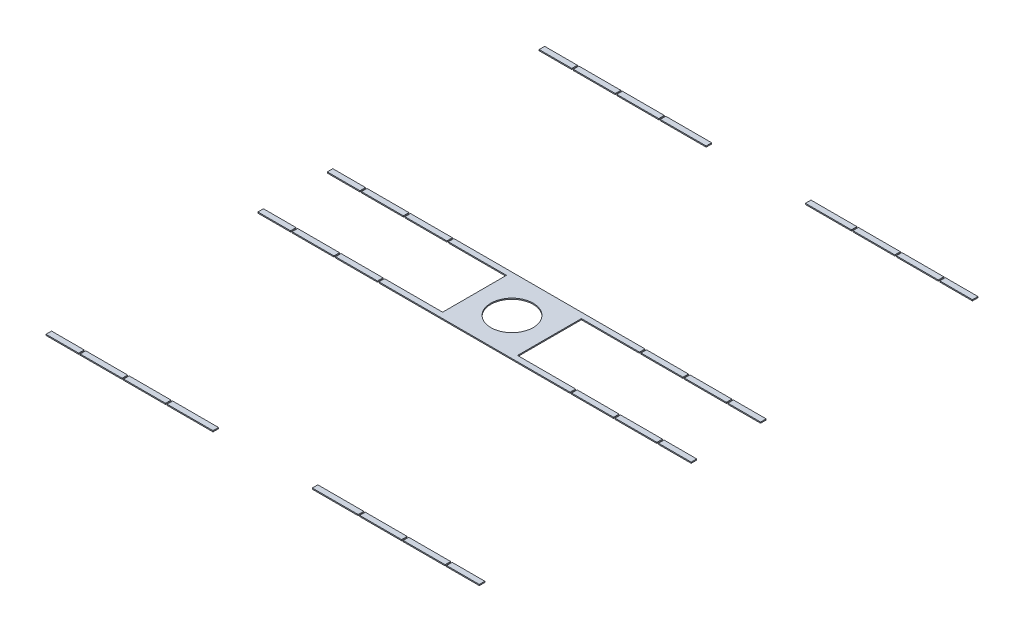
SolidWorks part; units mm, degrees
ref_plane "Front Plane" through (0, 0, 0) normal (0, 0, 1) x (1, 0, 0)
ref_plane "Top Plane" through (0, 0, 0) normal (0, 1, 0) x (1, 0, 0)
ref_plane "Right Plane" through (0, 0, 0) normal (1, 0, 0) x (0, 0, -1)
sketch "Sketch1" plane through (0, 0, 0) normal (0, 1, 0) x (1, 0, 0)
  line L0 (-55, 0) -> (55, 0) construction
  line L1 (-11.225, -11.225) -> (11.225, -11.225)
  line L2 (-11.225, -11.225) -> (-11.225, 11.225)
  line L3 (-11.225, 11.225) -> (11.225, 11.225)
  line L4 (11.225, -11.225) -> (11.225, 11.225)
  line L5 (-11.225, -11.225) -> (11.225, 11.225) construction
  line L6 (-11.225, 11.225) -> (11.225, -11.225) construction
  line L7 (-11.225, 11.225) -> (-1.725, 11.225)
  line L8 (-11.225, 11.225) -> (-11.225, 1.725)
  line L9 (-11.225, 1.725) -> (-1.725, 1.725)
  line L11 (-2.45, 11.73) -> (2.45, 11.73)
  line L12 (-11.225, -1.725) -> (-1.725, -1.725)
  line L13 (0, -55) -> (0, 55) construction
  line L14 (-11.73, -2.45) -> (-11.98, -2.45)
  line L15 (11.225, -1.725) -> (1.725, -1.725)
  line L16 (-11.73, -2.45) -> (-11.73, 2.45)
  line L17 (11.225, 1.725) -> (1.725, 1.725)
  line L18 (-1.725, 1.47) -> (-11.225, 1.47)
  line L19 (11.48, -11.48) -> (-11.48, -11.48)
  line L20 (11.48, -11.48) -> (11.48, 11.48)
  line L21 (11.48, 11.48) -> (-11.48, 11.48)
  line L22 (-11.48, -11.48) -> (-11.48, 11.48)
  line L23 (11.48, -11.48) -> (-11.48, 11.48) construction
  line L24 (11.48, 11.48) -> (-11.48, -11.48) construction
  line L25 (11.225, -1.47) -> (1.725, -1.47)
  line L26 (11.225, -1.47) -> (11.225, 1.47)
  line L27 (11.225, 1.47) -> (1.725, 1.47)
  line L28 (-11.225, -1.47) -> (-11.225, 1.47)
  line L29 (11.225, -1.47) -> (-11.225, 1.47) construction
  line L30 (11.225, 1.47) -> (-11.225, -1.47) construction
  line L31 (-1.225, -11.225) -> (1.225, -11.225)
  line L33 (-1.225, 11.225) -> (1.225, 11.225)
  line L35 (-11.73, 2.45) -> (-11.98, 2.45)
  line L36 (-11.98, -2.45) -> (-11.98, 2.45)
  line L38 (-1.725, -1.47) -> (-11.225, -1.47)
  line L40 (-11.48, 0) -> (-15.585, 0) construction
  line L41 (1.725, 1.725) -> (-1.725, 1.725)
  line L42 (1.725, 1.725) -> (1.725, -1.725)
  line L43 (1.725, -1.725) -> (-1.725, -1.725)
  line L44 (-1.725, 1.725) -> (-1.725, -1.725)
  line L45 (1.725, 1.725) -> (-1.725, -1.725) construction
  line L46 (1.725, -1.725) -> (-1.725, 1.725) construction
  line L47 (-11.48, -2.45) -> (-11.73, -2.45)
  line L48 (-11.48, 1.45) -> (-11.73, 1.45)
  line L49 (-11.48, 1.45) -> (-11.48, 2.45)
  line L50 (-11.48, 2.45) -> (-11.73, 2.45)
  line L51 (-11.73, 1.45) -> (-11.73, 2.45)
  line L52 (-11.73, -1.45) -> (-11.73, -2.45)
  line L53 (-11.48, -1.45) -> (-11.73, -1.45)
  line L54 (-11.48, -1.45) -> (-11.48, -2.45)
  line L55 (1.45, 11.48) -> (2.45, 11.48)
  line L56 (1.45, 11.48) -> (1.45, 11.73)
  line L57 (1.45, 11.73) -> (2.45, 11.73)
  line L58 (2.45, 11.48) -> (2.45, 11.73)
  line L59 (-2.45, 11.48) -> (-2.45, 11.73)
  line L60 (-1.45, 11.73) -> (-2.45, 11.73)
  line L61 (-1.45, 11.48) -> (-1.45, 11.73)
  line L62 (-1.45, 11.48) -> (-2.45, 11.48)
  line L63 (11.48, -1.45) -> (11.48, -2.45)
  line L64 (11.48, -1.45) -> (11.73, -1.45)
  line L65 (11.73, -1.45) -> (11.73, -2.45)
  line L66 (11.48, -2.45) -> (11.73, -2.45)
  line L67 (11.48, 2.45) -> (11.73, 2.45)
  line L68 (11.73, 1.45) -> (11.73, 2.45)
  line L69 (11.48, 1.45) -> (11.73, 1.45)
  line L70 (11.48, 1.45) -> (11.48, 2.45)
  line L71 (-1.45, -11.48) -> (-2.45, -11.48)
  line L72 (-1.45, -11.48) -> (-1.45, -11.73)
  line L73 (-1.45, -11.73) -> (-2.45, -11.73)
  line L74 (-2.45, -11.48) -> (-2.45, -11.73)
  line L75 (2.45, -11.48) -> (2.45, -11.73)
  line L76 (1.45, -11.73) -> (2.45, -11.73)
  line L77 (1.45, -11.48) -> (1.45, -11.73)
  line L78 (1.45, -11.48) -> (2.45, -11.48)
  line L79 (-2.45, 11.73) -> (-2.45, 11.98)
  line L80 (-2.45, 11.98) -> (2.45, 11.98)
  line L81 (2.45, 11.73) -> (2.45, 11.98)
  line L82 (11.73, 2.45) -> (11.73, -2.45)
  line L83 (11.73, 2.45) -> (11.98, 2.45)
  line L84 (11.98, 2.45) -> (11.98, -2.45)
  line L85 (11.73, -2.45) -> (11.98, -2.45)
  line L86 (2.45, -11.73) -> (-2.45, -11.73)
  line L87 (2.45, -11.73) -> (2.45, -11.98)
  line L88 (2.45, -11.98) -> (-2.45, -11.98)
  line L89 (-2.45, -11.73) -> (-2.45, -11.98)
  circle A0 centre (0, 0) radius 0.975
  point P0 (0, 0)
  point P77 (0, 0)
  point P89 (0, 0)
  dimension "D3" = 1.95
  dimension "D1" = 22.45
  dimension "D2" = 9.5
  dimension "D4" = 0.255
  dimension "D5" = 0.255
  dimension "D6" = 0.25
  dimension "D7" = 0.255
  dimension "D8" = 0.25
  dimension "D9" = 1.45
  dimension "D10" = 1
  dimension "D11" = 4
  dimension "D12" = 4
extrude "Boss-Extrude5" add sketch "Sketch1" along normal blind 0.05 contours L22 L19 L20 L21 L4 L1 L2 L3 | L44 L38 L2 L12 | L44 L9 L2 L18 | L41 L44 L43 L42 A0 | L17 L42 L27 L4 | L25 L42 L15 L4 | L47 L52 L53 L54 | L49 L48 L51 L50
sketch "Sketch2" plane through (0, 0.05, 0) normal (0, 1, 0) x (1, 0, 0)
  line L0 (-6.435, 1.225) -> (-6.435, 11.225) construction
  line L2 (-11.225, 11.225) -> (11.225, 11.225) construction
  line L3 (-11.225, 1.725) -> (11.225, 1.725) construction
  line L4 (-6.4, 1.225) -> (-6.47, 1.225)
  line L5 (-6.4, 1.225) -> (-6.4, 1.725)
  line L6 (-6.4, 1.725) -> (-6.47, 1.725)
  line L7 (-6.47, 1.225) -> (-6.47, 1.725)
  line L8 (-8.47, 1.725) -> (-8.4, 1.725)
  line L9 (-4.4, 1.225) -> (-4.47, 1.225)
  line L10 (-4.4, 1.225) -> (-4.4, 1.725)
  line L11 (-4.4, 1.725) -> (-4.47, 1.725)
  line L12 (-4.47, 1.225) -> (-4.47, 1.725)
  line L13 (-8.4, 1.225) -> (-8.4, 1.725)
  line L14 (-8.47, 1.225) -> (-8.4, 1.225)
  line L15 (-8.47, 1.225) -> (-8.47, 1.725)
  line L16 (-11.225, 6.475) -> (11.225, 6.475) construction
  line L17 (-11.225, 1.725) -> (-11.225, 11.225) construction
  line L18 (11.225, 1.725) -> (11.225, 11.225) construction
  line L19 (-8.4, 1.725) -> (-6.47, 1.725) construction
  line L20 (-4.4, 11.225) -> (-4.47, 11.225)
  line L21 (-4.47, 11.725) -> (-4.47, 11.225)
  line L22 (-4.4, 11.725) -> (-4.47, 11.725)
  line L23 (-4.4, 11.725) -> (-4.4, 11.225)
  line L24 (-6.4, 11.225) -> (-6.47, 11.225)
  line L25 (-6.47, 11.725) -> (-6.47, 11.225)
  line L26 (-6.4, 11.725) -> (-6.47, 11.725)
  line L27 (-6.4, 11.725) -> (-6.4, 11.225)
  line L28 (-8.47, 11.725) -> (-8.47, 11.225)
  line L29 (-8.47, 11.725) -> (-8.4, 11.725)
  line L30 (-8.4, 11.725) -> (-8.4, 11.225)
  line L31 (-8.47, 11.225) -> (-8.4, 11.225)
  line L32 (0, -55) -> (0, 55) construction
  line L33 (4.4, 1.725) -> (4.47, 1.725)
  line L34 (4.47, 1.225) -> (4.47, 1.725)
  line L35 (4.4, 1.225) -> (4.47, 1.225)
  line L36 (4.4, 1.225) -> (4.4, 1.725)
  line L37 (6.4, 1.725) -> (6.47, 1.725)
  line L38 (6.47, 1.225) -> (6.47, 1.725)
  line L39 (6.4, 1.225) -> (6.47, 1.225)
  line L40 (6.4, 1.225) -> (6.4, 1.725)
  line L41 (8.47, 1.225) -> (8.47, 1.725)
  line L42 (8.47, 1.225) -> (8.4, 1.225)
  line L43 (8.4, 1.225) -> (8.4, 1.725)
  line L44 (8.47, 1.725) -> (8.4, 1.725)
  line L45 (4.4, 11.725) -> (4.4, 11.225)
  line L46 (4.4, 11.725) -> (4.47, 11.725)
  line L47 (4.47, 11.725) -> (4.47, 11.225)
  line L48 (4.4, 11.225) -> (4.47, 11.225)
  line L49 (6.4, 11.725) -> (6.4, 11.225)
  line L50 (6.4, 11.725) -> (6.47, 11.725)
  line L51 (6.47, 11.725) -> (6.47, 11.225)
  line L52 (6.4, 11.225) -> (6.47, 11.225)
  line L53 (8.47, 11.725) -> (8.4, 11.725)
  line L54 (8.4, 11.725) -> (8.4, 11.225)
  line L55 (8.47, 11.225) -> (8.4, 11.225)
  line L56 (8.47, 11.725) -> (8.47, 11.225)
  line L57 (-55, 0) -> (55, 0) construction
  line L58 (-8.47, -11.725) -> (-8.4, -11.725)
  line L59 (-8.4, -11.725) -> (-8.4, -11.225)
  line L60 (-8.47, -11.225) -> (-8.4, -11.225)
  line L61 (-8.47, -11.725) -> (-8.47, -11.225)
  line L62 (-6.4, -11.725) -> (-6.4, -11.225)
  line L63 (-6.4, -11.725) -> (-6.47, -11.725)
  line L64 (-6.47, -11.725) -> (-6.47, -11.225)
  line L65 (-6.4, -11.225) -> (-6.47, -11.225)
  line L66 (-4.4, -11.725) -> (-4.4, -11.225)
  line L67 (-4.4, -11.725) -> (-4.47, -11.725)
  line L68 (-4.47, -11.725) -> (-4.47, -11.225)
  line L69 (-4.4, -11.225) -> (-4.47, -11.225)
  line L70 (4.4, -11.725) -> (4.47, -11.725)
  line L71 (4.47, -11.725) -> (4.47, -11.225)
  line L72 (4.4, -11.225) -> (4.47, -11.225)
  line L73 (4.4, -11.725) -> (4.4, -11.225)
  line L74 (6.4, -11.725) -> (6.47, -11.725)
  line L75 (6.47, -11.725) -> (6.47, -11.225)
  line L76 (6.4, -11.225) -> (6.47, -11.225)
  line L77 (6.4, -11.725) -> (6.4, -11.225)
  line L78 (8.47, -11.725) -> (8.47, -11.225)
  line L79 (8.47, -11.225) -> (8.4, -11.225)
  line L80 (8.4, -11.725) -> (8.4, -11.225)
  line L81 (8.47, -11.725) -> (8.4, -11.725)
  line L82 (8.47, -1.225) -> (8.4, -1.225)
  line L83 (8.4, -1.225) -> (8.4, -1.725)
  line L84 (8.47, -1.725) -> (8.4, -1.725)
  line L85 (8.47, -1.225) -> (8.47, -1.725)
  line L86 (6.4, -1.225) -> (6.4, -1.725)
  line L87 (6.4, -1.225) -> (6.47, -1.225)
  line L88 (6.47, -1.225) -> (6.47, -1.725)
  line L89 (6.4, -1.725) -> (6.47, -1.725)
  line L90 (4.4, -1.225) -> (4.4, -1.725)
  line L91 (4.4, -1.225) -> (4.47, -1.225)
  line L92 (4.47, -1.225) -> (4.47, -1.725)
  line L93 (4.4, -1.725) -> (4.47, -1.725)
  line L94 (-4.4, -1.725) -> (-4.47, -1.725)
  line L95 (-4.47, -1.225) -> (-4.47, -1.725)
  line L96 (-4.4, -1.225) -> (-4.47, -1.225)
  line L97 (-4.4, -1.225) -> (-4.4, -1.725)
  line L98 (-6.4, -1.725) -> (-6.47, -1.725)
  line L99 (-6.47, -1.225) -> (-6.47, -1.725)
  line L100 (-6.4, -1.225) -> (-6.47, -1.225)
  line L101 (-6.4, -1.225) -> (-6.4, -1.725)
  line L102 (-8.47, -1.225) -> (-8.47, -1.725)
  line L103 (-8.47, -1.225) -> (-8.4, -1.225)
  line L104 (-8.4, -1.225) -> (-8.4, -1.725)
  line L105 (-8.47, -1.725) -> (-8.4, -1.725)
  point P12 (-6.435, 1.225)
  dimension "D1" = 0.07
  dimension "D2" = 2
  dimension "D3" = 0.5
extrude "Cut-Extrude1" cut sketch "Sketch2" against normal blind 10 contours L28 L31 L30 L29 | L24 L25 L26 L27 | L20 L21 L22 L23 | L45 L48 L47 L46 | L49 L52 L51 L50 | L53 L54 L55 L56 | L41 L44 L43 L42 | L37 L38 L39 L40 | L33 L34 L35 L36 | L90 L93 L92 L91 | L86 L89 L88 L87 | L82 L83 L84 L85 | L78 L79 L80 L81 | L74 L75 L76 L77 | L70 L71 L72 L73 | L66 L69 L68 L67 | L62 L65 L64 L63 | L58 L59 L60 L61 | L102 L105 L104 L103 | L98 L99 L100 L101 | L94 L95 L96 L97 | L10 L9 L12 L11 | L5 L4 L7 L6 | L8 L13 L14 L15
sketch "Sketch3" plane through (0, 0.05, 0) normal (0, 1, 0) x (1, 0, 0)
  line L0 (-8.47, -11.48) -> (-11.48, -11.48) construction
  line L1 (-9.975, -11.48) -> (-11.73, -11.48)
  line L2 (-9.975, -11.48) -> (-9.975, 11.48)
  line L3 (-9.975, 11.48) -> (-11.73, 11.48)
  line L4 (-11.73, -11.48) -> (-11.73, 11.48)
  line L5 (-8.47, 11.48) -> (-11.48, 11.48) construction
  line L6 (-11.73, -1.45) -> (-11.73, -2.45) construction
  line L7 (0, 0) -> (0, 11.48) construction
  line L8 (4.4, 11.48) -> (-4.4, 11.48) construction
  line L9 (-11.225, 1.725) -> (-8.47, 1.725) construction
  line L10 (2.2862, 11.48) -> (-2.2862, 11.48)
  line L11 (0, 11.48) -> (0, 1.725)
  line L12 (2.2862, 1.725) -> (-2.2862, 1.725)
  line L13 (-2.2862, 11.48) -> (-2.2862, 1.725)
  line L14 (-55, 0) -> (55, 0) construction
  line L15 (2.2862, -1.725) -> (-2.2862, -1.725)
  line L16 (-2.2862, -11.48) -> (-2.2862, -1.725)
  line L17 (2.2862, -11.48) -> (-2.2862, -11.48)
  line L18 (0, -11.48) -> (0, -1.725)
  line L19 (0, -55) -> (0, 55) construction
  line L20 (2.2862, -11.48) -> (2.2862, -1.725)
  line L21 (2.2862, 11.48) -> (2.2862, 1.725)
  line L22 (9.975, 11.48) -> (11.73, 11.48)
  line L23 (11.73, -11.48) -> (11.73, 11.48)
  line L24 (9.975, -11.48) -> (11.73, -11.48)
  line L25 (9.975, -11.48) -> (9.975, 11.48)
  line M16 (4.4, 1.725) -> (-4.4, 1.725)
extrude "Cut-Extrude2" cut sketch "Sketch3" against normal blind 10 contours L4 L1 L2 L3 | L10 L13 L11 M16 | L21 L10 L11 M16 | L17 L20 L15 L18 | L25 L24 L23 L22
